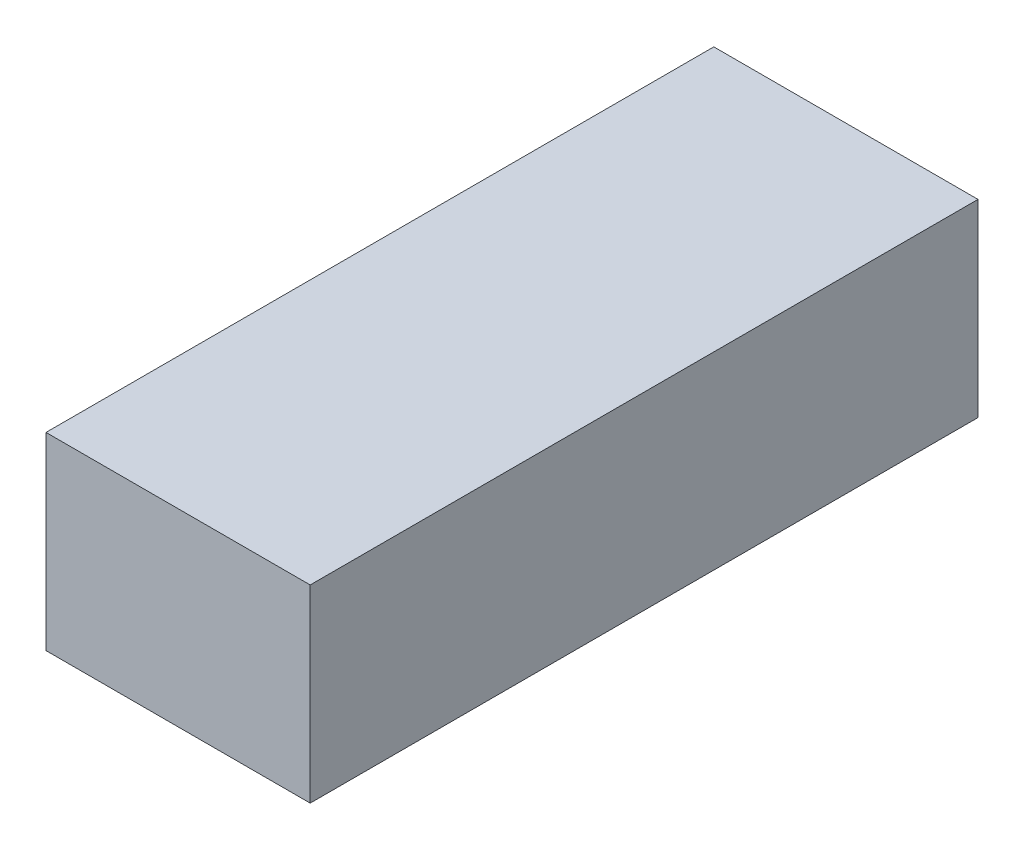
SolidWorks part; units mm, degrees
ref_plane "Front Plane" through (0, 0, 0) normal (0, 0, 1) x (1, 0, 0)
ref_plane "Top Plane" through (0, 0, 0) normal (0, 1, 0) x (1, 0, 0)
ref_plane "Right Plane" through (0, 0, 0) normal (1, 0, 0) x (0, 0, -1)
sketch "Sketch1" plane through (0, 0, 0) normal (0, 1, 0) x (1, 0, 0)
  line L0 (0, -44.7868) -> (0, 44.7868) construction
  line L1 (-36, 91) -> (36, 91)
  line L2 (-36, 91) -> (-36, -91)
  line L3 (-36, -91) -> (36, -91)
  line L4 (36, 91) -> (36, -91)
  line L5 (-44.2539, 0) -> (44.2539, 0) construction
  dimension "D1" = 182
  dimension "D2" = 72
  dimension "D3" = 36
  dimension "D4" = 91
extrude "Boss-Extrude1" add sketch "Sketch1" along normal mid plane 51.5
